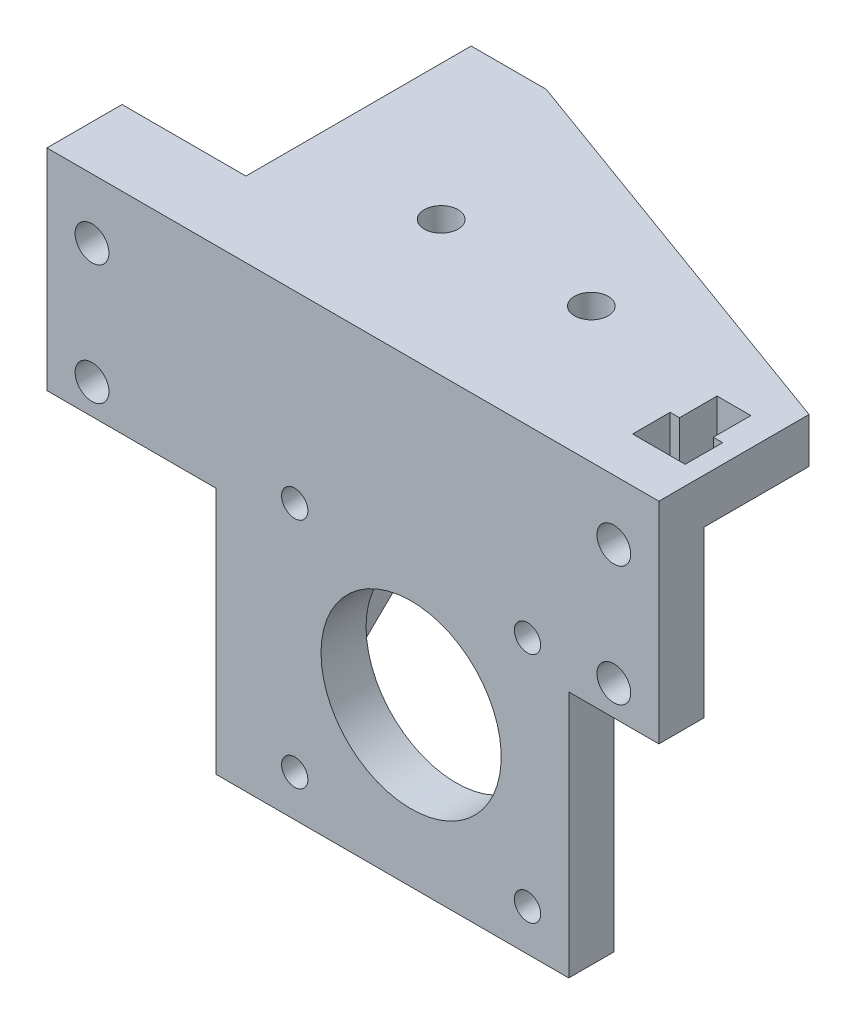
SolidWorks part; units mm, degrees
material "Printed PLA"
ref_plane "Front Plane" through (0, 0, 0) normal (0, 0, 1) x (1, 0, 0)
ref_plane "Top Plane" through (0, 0, 0) normal (0, 1, 0) x (1, 0, 0)
ref_plane "Right Plane" through (0, 0, 0) normal (1, 0, 0) x (0, 0, -1)
sketch "Sketch2" plane through (0, 0, 0) normal (0, 1, 0) x (1, 0, 0)
  line L0 (-16.5, 0) -> (0, 0)
  line L1 (0, 0) -> (0, 30)
  line L2 (0, 30) -> (10, 30)
  line L3 (10, 30) -> (10, -10)
  line L4 (10, -10) -> (-16.5, -10)
  line L5 (-16.5, -10) -> (-16.5, 0)
  dimension "D1" = 10
  dimension "D2" = 16.5
  dimension "D3" = 30
extrude "Boss-Extrude1" add sketch "Sketch2" along normal blind 28
sketch "Sketch3" plane through (0, 28, 0) normal (0, 1, 0) x (1, 0, 0)
  line L1 (10, -10) -> (53, -10)
  line L2 (10, -10) -> (10, -4)
  line L3 (10, -4) -> (53, -4)
  line L4 (53, -10) -> (53, -4)
  dimension "D1" = 6
  dimension "D2" = 43
extrude "Boss-Extrude2" add sketch "Sketch3" against normal blind 61
sketch "Sketch4" plane through (0, 0, 4) normal (0, 0, -1) x (-1, 0, 0)
  line L0 (-47.5, 3.5) -> (-47.5, -27.5) construction
  line L1 (-47.5, -27.5) -> (-16.5, -27.5) construction
  line L2 (-16.5, -27.5) -> (-16.5, 3.5) construction
  line L3 (-16.5, 3.5) -> (-47.5, 3.5) construction
  line L4 (-47.5, 3.5) -> (-16.5, -27.5) construction
  line L5 (-10, 28) -> (-10, 0) construction
  line L6 (-53, 28) -> (-10, 28) construction
  circle A0 centre (-32, -12) radius 12
  circle A1 centre (-16.5, 3.5) radius 1.75
  circle A2 centre (-16.5, -27.5) radius 1.75
  circle A3 centre (-47.5, -27.5) radius 1.75
  circle A4 centre (-47.5, 3.5) radius 1.75
  dimension "D2" = 24
  dimension "D3" = 3.5
  dimension "D1" = 31
  dimension "D4" = 22
  dimension "D5" = 40
extrude "Cut-Extrude1" cut sketch "Sketch4" against normal through all
sketch "Sketch6" plane through (-16.5, 0, 0) normal (-1, 0, 0) x (0, 0, 1)
  line L0 (10, 28) -> (10, 0)
  line L1 (10, 0) -> (18, 0)
  line L2 (18, 0) -> (18, 8)
  line L3 (18, 16) -> (18, 28)
  line L4 (18, 28) -> (10, 28)
  line L5 (18, 12) -> (0, 12) construction
  line L8 (0, 28) -> (0, 0) construction
  arc A0 (18, 8) -> (18, 16) centre (18, 12) cw
  dimension "D1" = 4
  dimension "D2" = 18
  dimension "D3" = 16
extrude "Boss-Extrude3" add sketch "Sketch6" against normal blind 12
sketch "Sketch7" plane through (53, 0, 0) normal (1, 0, 0) x (0, 0, -1)
  line L0 (-18, 8) -> (-18, 0)
  line L1 (-4, 28) -> (-18, 28)
  line L2 (-4, 28) -> (-4, 0)
  line L3 (-4, 0) -> (-18, 0)
  line L4 (-18, 28) -> (-18, 16)
  arc A0 (-18, 8) -> (-18, 16) centre (-18, 12) ccw
  arc A1 (-18, 8) -> (-18, 16) centre (-18, 12) ccw construction
extrude "Boss-Extrude4" add sketch "Sketch7" along normal blind 12
sketch "Sketch5" plane through (0, 0, 18) normal (0, 0, 1) x (1, 0, 0)
  line L0 (-10.5, 20) -> (-10.5, 4) construction
  line L1 (-16.5, 12) -> (-10.5, 12) construction
  line L4 (-16.5, 16) -> (-16.5, 8) construction
  line L5 (-4.5, 0) -> (53, 0) construction
  line L6 (24.25, 0) -> (24.25, 20) construction
  line L7 (65, 12) -> (59, 12) construction
  line L8 (59, 20) -> (59, 4) construction
  circle A0 centre (-10.5, 20) radius 2.25
  circle A1 centre (-10.5, 4) radius 2.25
  circle A2 centre (59, 4) radius 2.25
  circle A3 centre (59, 20) radius 2.25
  dimension "D1" = 4.5
  dimension "D2" = 16
  dimension "D3" = 6
extrude "Cut-Extrude2" cut sketch "Sketch5" against normal through all
sketch "Sketch8" plane through (0, 28, 0) normal (0, 1, 0) x (1, 0, 0)
  line L1 (10, 30) -> (65, 30)
  line L2 (10, 30) -> (10, -4)
  line L3 (10, -4) -> (65, -4)
  line L4 (65, 30) -> (65, -4)
extrude "Boss-Extrude5" add sketch "Sketch8" against normal blind 6
sketch "Sketch9" plane through (0, 22, 0) normal (0, -1, 0) x (1, 0, 0)
  line L0 (65, 4) -> (53, 4) construction
  line L1 (55.5, 4) -> (62.5, 4)
  line L2 (55.5, 4) -> (55.5, -1)
  line L3 (55.5, -1) -> (56.75, -1)
  line L4 (62.5, 4) -> (62.5, -1)
  line L5 (61.25, -1) -> (62.5, -1)
  line L6 (59, -6) -> (59, 18) construction
  line L7 (56.75, -1) -> (56.75, -6)
  line L8 (56.75, -6) -> (61.25, -6)
  line L9 (61.25, -1) -> (61.25, -6)
  line L10 (65, 18) -> (53, 18) construction
  dimension "D1" = 4.5
  dimension "D2" = 7
  dimension "D3" = 5
  dimension "D4" = 5
extrude "Cut-Extrude3" cut sketch "Sketch9" against normal through all
sketch "Sketch10" plane through (10, 0, 0) normal (-1, 0, 0) x (0, 0, 1)
  line L0 (-30, 0) -> (4, -33)
  line L1 (4, -33) -> (10, -33)
  line L2 (10, -33) -> (10, -18.4412) construction
  line L3 (10, -33) -> (10, 0) construction
  line L4 (10, -18.4412) -> (4, -18.4412) construction
  line L5 (4, -33) -> (4, 0) construction
  line L6 (4, -18.4412) -> (-15, 0) construction
  line L7 (-30, 0) -> (0, 0) construction
  line L8 (-15, 0) -> (-30, 0)
  line L9 (4, -18.4412) -> (10, -24.2647) construction
  line L10 (10, -24.2647) -> (10, -33)
  line L11 (-15, 0) -> (10, 0)
  line L12 (10, 0) -> (10, -24.2647)
extrude "Boss-Extrude6" add sketch "Sketch10" along normal blind 4
sketch "Sketch11" plane through (10, 0, 0) normal (1, 0, 0) x (0, 0, -1)
  line L0 (24, 17.5) -> (12, 17.5) construction
  line L1 (-4, 22) -> (30, 22) construction
  line L2 (30, 22) -> (30, 0) construction
  circle A0 centre (12, 17.5) radius 2.25 construction
  circle A1 centre (24, 17.5) radius 2.25
  point P4 (13, 22)
  dimension "D1" = 4.5
  dimension "D2" = 12
  dimension "D3" = 4.5
  dimension "D4" = 6
extrude "Cut-Extrude4" cut sketch "Sketch11" against normal through all
sketch "Sketch12" plane through (0, 22, 0) normal (0, -1, 0) x (1, 0, 0)
  line L0 (38, -8) -> (18, -8) construction
  line L1 (53, 4) -> (10, 4) construction
  line L2 (10, -30) -> (10, 4) construction
  circle A0 centre (18, -8) radius 2.25
  circle A1 centre (38, -8) radius 2.25
  dimension "D1" = 4.5
  dimension "D4" = 8
  dimension "D2" = 20
  dimension "D3" = 12
extrude "Cut-Extrude5" cut sketch "Sketch12" against normal up to next
sketch "Sketch13" plane through (0, 22, 0) normal (0, -1, 0) x (1, 0, 0)
  line L0 (10, -30) -> (65, -10)
  line L1 (65, 4) -> (65, -30) construction
  line L2 (65, -10) -> (65, -30)
  line L3 (65, -30) -> (10, -30) construction
  line L4 (65, -30) -> (10, -30)
  dimension "D1" = 20
extrude "Cut-Extrude6" cut sketch "Sketch13" against normal through all
sketch "Sketch14" plane through (-16.5, 0, 0) normal (-1, 0, 0) x (0, 0, 1)
  line L1 (10, 0) -> (18, 0)
  line L2 (10, 0) -> (10, 28)
  line L3 (10, 28) -> (18, 28)
  line L4 (18, 0) -> (18, 28)
extrude "Cut-Extrude7" cut sketch "Sketch14" against normal through all
